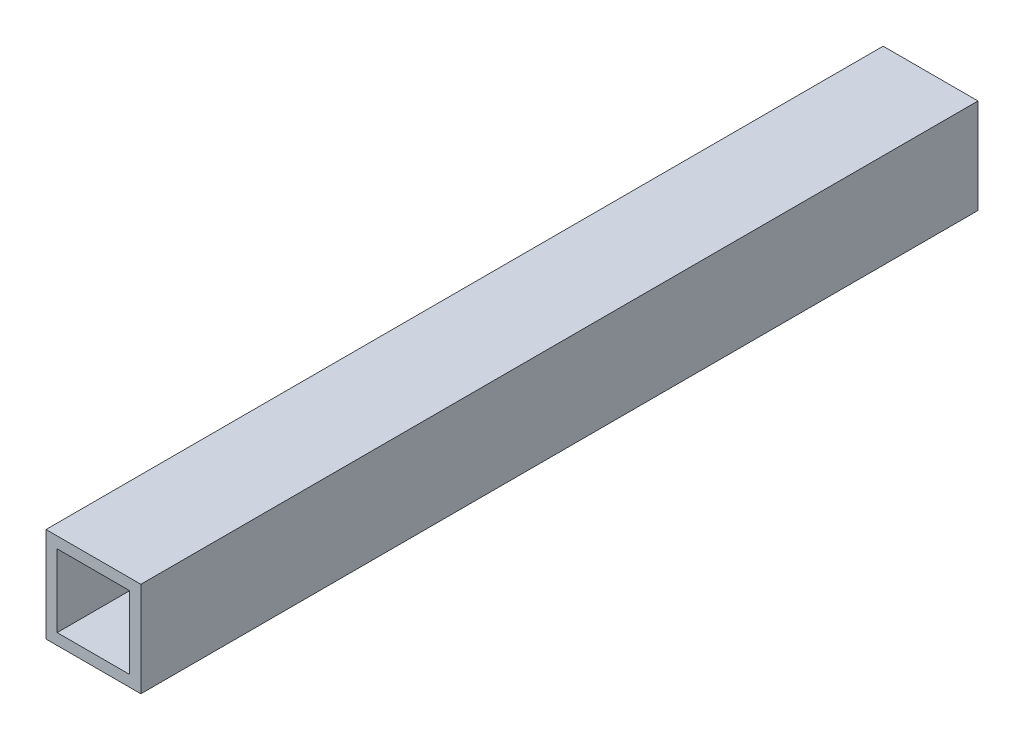
SolidWorks part; units mm, degrees
ref_plane "Front Plane" through (0, 0, 0) normal (0, 0, 1) x (1, 0, 0)
ref_plane "Top Plane" through (0, 0, 0) normal (0, 1, 0) x (1, 0, 0)
ref_plane "Right Plane" through (0, 0, 0) normal (1, 0, 0) x (0, 0, -1)
sketch "Sketch1" plane through (0, 0, 0) normal (0, 0, 1) x (1, 0, 0)
  line L0 (-6.5, -6.5) -> (-6.5, 6.5)
  line L1 (-8.5, -8.5) -> (8.5, -8.5)
  line L2 (-8.5, -8.5) -> (-8.5, 8.5)
  line L3 (-8.5, 8.5) -> (8.5, 8.5)
  line L4 (8.5, -8.5) -> (8.5, 8.5)
  line L5 (-8.5, -8.5) -> (8.5, 8.5) construction
  line L6 (-8.5, 8.5) -> (8.5, -8.5) construction
  line L7 (-6.5, 6.5) -> (6.5, 6.5)
  line L8 (6.5, -6.5) -> (6.5, 6.5)
  line L9 (-6.5, -6.5) -> (6.5, -6.5)
  point P0 (0, 0)
  dimension "D1" = 17
  dimension "D2" = 17
  dimension "D3" = 2
extrude "Boss-Extrude1" add sketch "Sketch1" along normal blind 150
